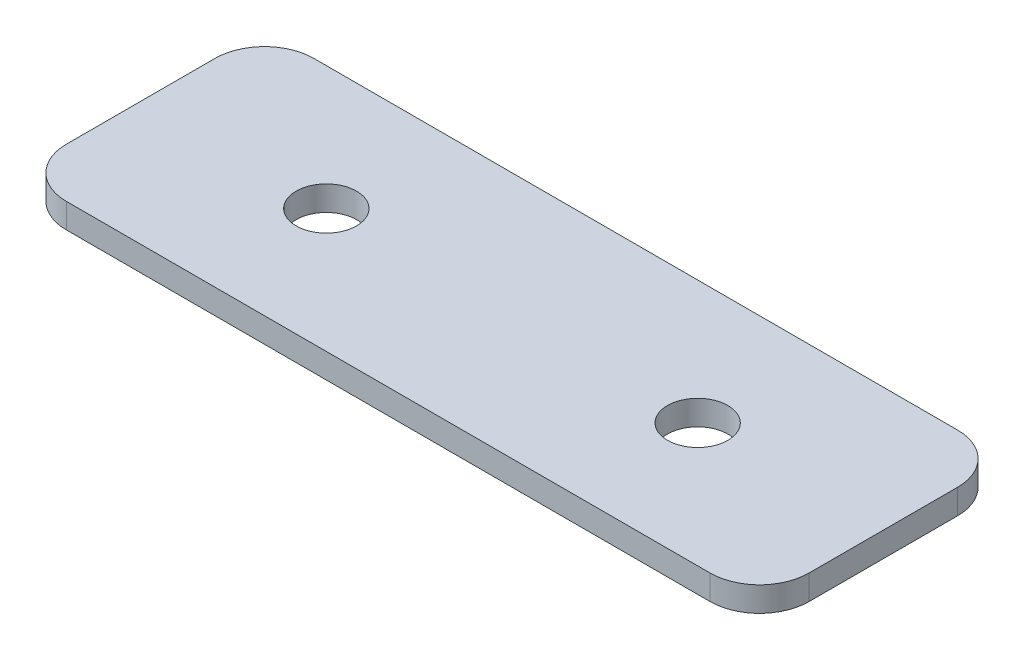
SolidWorks part; units mm, degrees
ref_plane "Front" through (0, 0, 0) normal (0, 0, 1) x (1, 0, 0)
ref_plane "Top" through (0, 0, 0) normal (0, 1, 0) x (1, 0, 0)
ref_plane "Right" through (0, 0, 0) normal (1, 0, 0) x (0, 0, -1)
sketch "Sketch2" plane through (0, 0, 0) normal (0, 1, 0) x (1, 0, 0)
  line L0 (-15, -5) -> (15, -5)
  line L1 (7.5, 0) -> (-7.5, 0) construction
  line L2 (0, 0) -> (0, 5) construction
  line L6 (15, -5) -> (15, 5)
  line L7 (15, 5) -> (-15, 5)
  line L8 (-15, 5) -> (-15, -5)
  circle A2 centre (7.5, 0) radius 1.2192
  circle A9 centre (-7.5, 0) radius 1.2192
  point P1 (0, 0)
  point P2 (-15, -5)
  dimension "D3" = 2.4384
  dimension "D1" = 30
  dimension "D2" = 15
  dimension "D4" = 5
  dimension "D5" = 10
extrude "Boss-Extrude1" add sketch "Sketch2" along normal blind 1
fillet "Fillet1" radius 2 4 edges at (-15, 0.5, -5) (-15, 0.5, 5) (15, 0.5, -5) (15, 0.5, 5)
